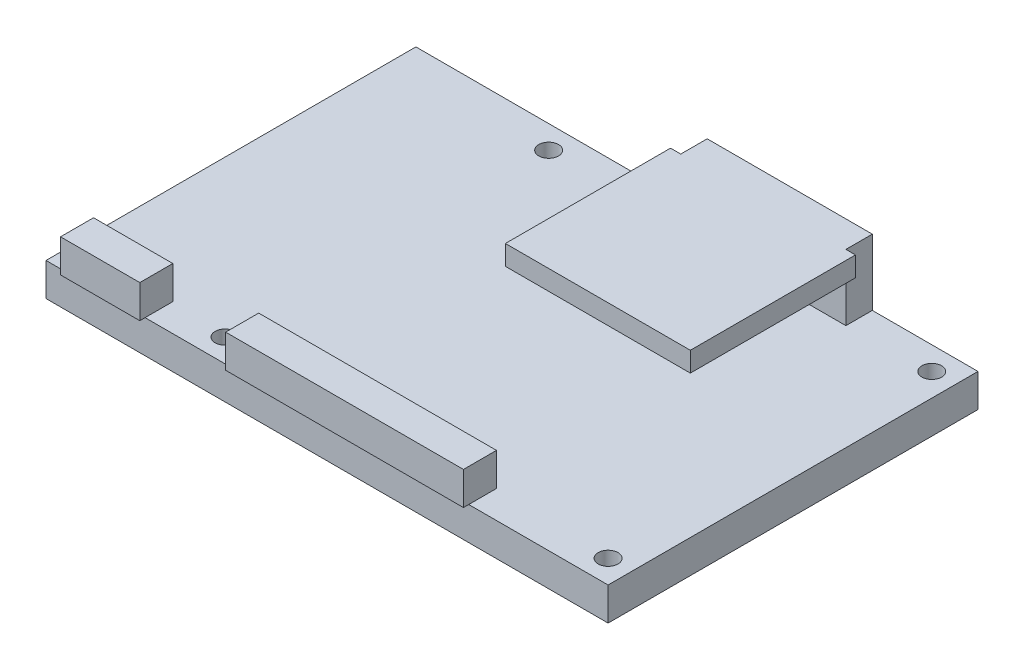
SolidWorks part; units mm, degrees
ref_plane "前视基准面" through (0, 0, 0) normal (0, 0, 1) x (1, 0, 0)
ref_plane "上视基准面" through (0, 0, 0) normal (0, 1, 0) x (1, 0, 0)
ref_plane "右视基准面" through (0, 0, 0) normal (1, 0, 0) x (0, 0, -1)
sketch "Sketch1" plane through (0, 0, 0) normal (0, 1, 0) x (1, 0, 0)
  line L1 (-42.55, -28) -> (42.55, -28)
  line L2 (-42.55, -28) -> (-42.55, 28)
  line L3 (-42.55, 28) -> (42.55, 28)
  line L4 (42.55, -28) -> (42.55, 28)
  line L5 (-42.55, -28) -> (42.55, 28) construction
  line L6 (-42.55, 28) -> (42.55, -28) construction
  circle A0 centre (-18.95, -24.5) radius 1.5
  circle A1 centre (39.05, -24.5) radius 1.5
  circle A2 centre (39.05, 24.5) radius 1.5
  circle A3 centre (-18.95, 24.5) radius 1.5
  point P0 (0, 0)
  point P8 (0, 0)
  point P9 (0, 0)
  dimension "D3" = 3
  dimension "D1" = 56
  dimension "D2" = 85.1
  dimension "D4" = 23.6
  dimension "D5" = 3.5
  dimension "D8" = 58
  dimension "D9" = 49
  dimension "D6" = 2
  dimension "D7" = 2
extrude "Boss-Extrude1" add sketch "Sketch1" along normal blind 5
sketch "Sketch3" plane through (0, 5, 0) normal (0, 1, 0) x (1, 0, 0)
  line L0 (-42.55, 28) -> (-42.55, -28) construction
  line L1 (-39.55, -28.8) -> (-27.55, -28.8)
  line L2 (-39.55, -28.8) -> (-39.55, -23.8)
  line L3 (-39.55, -23.8) -> (-27.55, -23.8)
  line L4 (-27.55, -28.8) -> (-27.55, -23.8)
  line L5 (-42.55, -28) -> (42.55, -28) construction
  line L6 (-14.55, -28.8) -> (-14.55, -23.8)
  line L7 (-14.55, -28.8) -> (-2.55, -28.8)
  line L8 (-2.55, -28.8) -> (-2.55, -23.8)
  line L9 (-14.55, -23.8) -> (-2.55, -23.8)
  line L10 (-2.55, -28.8) -> (-2.55, -23.8)
  line L11 (-2.55, -23.8) -> (9.45, -23.8)
  line L12 (9.45, -28.8) -> (9.45, -23.8)
  line L13 (-2.55, -28.8) -> (9.45, -28.8)
  line L14 (9.45, -28.8) -> (9.45, -23.8)
  line L15 (9.45, -23.8) -> (21.45, -23.8)
  line L16 (21.45, -28.8) -> (21.45, -23.8)
  line L17 (9.45, -28.8) -> (21.45, -28.8)
  point P22 (0, 0)
  dimension "D1" = 5
  dimension "D2" = 12
  dimension "D3" = 3
  dimension "D4" = 0.8
  dimension "D7" = 49
  dimension "D8" = 13
  dimension "D5" = 2
  dimension "D6" = 3
extrude "Boss-Extrude2" add sketch "Sketch3" along normal blind 5 contours L3 L4 L1 L2 | L9 L8 L7 L6 | L11 L12 L13 L10 | L17 L16 L15 L14
sketch "Sketch4" plane through (0, 5, 0) normal (0, 1, 0) x (1, 0, 0)
  line L0 (42.55, 28) -> (-42.55, 28) construction
  line L1 (1.55, 28) -> (26.55, 28)
  line L2 (1.55, 28) -> (1.55, 24)
  line L3 (1.55, 24) -> (26.55, 24)
  line L4 (26.55, 28) -> (26.55, 24)
  line L5 (42.55, -28) -> (42.55, 28) construction
  dimension "D1" = 25
  dimension "D2" = 4
  dimension "D3" = 16
extrude "Boss-Extrude3" add sketch "Sketch4" along normal blind 10
sketch "Sketch5" plane through (0, 0, -24) normal (0, 0, 1) x (1, 0, 0)
  line L7 (0, 15) -> (28, 15)
  line L8 (0, 15) -> (0, 12)
  line L9 (0, 12) -> (28, 12)
  line L10 (28, 15) -> (28, 12)
  line L11 (14, 20.1221) -> (14, 0.8896) construction
  point P4 (0, 0)
  dimension "D1" = 3
  dimension "D2" = 28
  dimension "D3" = 12
extrude "Boss-Extrude4" add sketch "Sketch5" along normal blind 25
